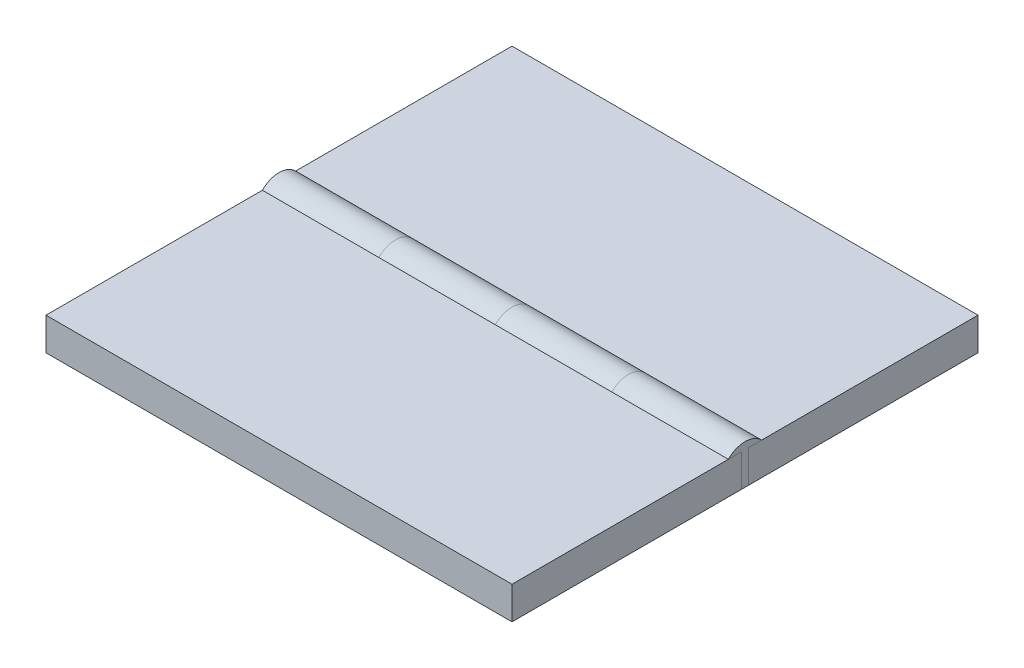
SolidWorks part; units mm, degrees
ref_plane "Front Plane" through (0, 0, 0) normal (0, 0, 1) x (1, 0, 0)
ref_plane "Top Plane" through (0, 0, 0) normal (0, 1, 0) x (1, 0, 0)
ref_plane "Right Plane" through (0, 0, 0) normal (1, 0, 0) x (0, 0, -1)
sketch "Sketch1" plane through (0, 0, 0) normal (1, 0, 0) x (0, 0, -1)
  line L0 (0, 0) -> (0.75, 0) construction
  line L1 (-50, -3.5) -> (-0.75, -3.5)
  line L2 (-50, -3.5) -> (-50, 3.5)
  line L3 (-50, 3.5) -> (-0.75, 3.5)
  line L4 (50, -3.5) -> (50, 3.5)
  line L5 (-50, -3.5) -> (50, 3.5) construction
  line L6 (-50, 3.5) -> (50, -3.5) construction
  line L7 (0.75, 3.5) -> (0.75, -3.5)
  line L8 (0, 0) -> (-0.75, 0) construction
  line L9 (-0.75, -3.5) -> (-0.75, 3.5)
  line L10 (0.75, 3.5) -> (50, 3.5)
  line L11 (0.75, -3.5) -> (50, -3.5)
  line L12 (-0.75, -3.5) -> (0.75, -3.5)
  arc A0 (3.5707, 3.5) -> (-3.5707, 3.5) centre (0, 0) ccw
  point P0 (0, 0)
  dimension "D5" = 10
  dimension "D1" = 100
  dimension "D2" = 7
  dimension "D3" = 0.75
  dimension "D4" = 0.75
extrude "Boss-Extrude1" add sketch "Sketch1" along normal blind 100 contours L1 L9 L3 L2 | L7 L11 L4 L10
sketch "Sketch2" plane through (0, 0, 0) normal (-1, 0, 0) x (0, 0, 1)
  line L0 (0.75, -3.5) -> (-0.75, -3.5) construction
  line L1 (-0.75, 3.5) -> (-0.75, -3.5) construction
  line L2 (-0.75, 3.5) -> (-50, 3.5) construction
  line L3 (-50, -3.5) -> (-50, 3.5) construction
  line L4 (-0.75, -3.5) -> (-50, -3.5) construction
  line L5 (50, -3.5) -> (0.75, -3.5) construction
  line L6 (50, -3.5) -> (50, 3.5) construction
  line L7 (50, 3.5) -> (0.75, 3.5) construction
  line L8 (0.75, -3.5) -> (0.75, 3.5) construction
  line L9 (0.75, -3.5) -> (-0.75, -3.5)
  line L10 (-0.75, 3.5) -> (-0.75, -3.5)
  line L11 (-0.75, 3.5) -> (-50, 3.5)
  line L12 (-50, -3.5) -> (-50, 3.5)
  line L13 (-0.75, -3.5) -> (-50, -3.5)
  line L14 (50, -3.5) -> (0.75, -3.5)
  line L15 (50, -3.5) -> (50, 3.5)
  line L16 (50, 3.5) -> (0.75, 3.5)
  line L17 (0.75, -3.5) -> (0.75, 3.5)
  arc A0 (3.5707, 3.5) -> (-3.5707, 3.5) centre (0, 0) ccw construction
  arc A1 (3.5707, 3.5) -> (-3.5707, 3.5) centre (0, 0) ccw
  line M1 (-0.75, -3.5) -> (-0.75, 3.5)
  line M2 (-0.75, 3.5) -> (-50, 3.5)
extrude "Boss-Extrude2" add sketch "Sketch2" against normal blind 25 separate body contours L16 A1 L9 L17 M2 M1
sketch "Sketch3" plane through (25, 0, 0) normal (1, 0, 0) x (0, 0, -1)
  line L5 (-3.5707, 3.5) -> (-0.75, 3.5)
  line L6 (-0.75, 3.5) -> (-0.75, -3.5)
  line L7 (-0.75, -3.5) -> (0.75, -3.5)
  line L8 (0.75, -3.5) -> (0.75, 3.5)
  line L9 (0.75, 3.5) -> (3.5707, 3.5)
  line L10 (-3.5707, 3.5) -> (-0.75, 3.5)
  line L11 (-0.75, 3.5) -> (-0.75, -3.5)
  line L12 (-0.75, -3.5) -> (0.75, -3.5)
  line L13 (0.75, -3.5) -> (0.75, 3.5)
  line L14 (0.75, 3.5) -> (3.5707, 3.5)
  arc A1 (3.5707, 3.5) -> (-3.5707, 3.5) centre (0, 0) ccw
  arc A2 (3.5707, 3.5) -> (-3.5707, 3.5) centre (0, 0) ccw
  dimension "D1" = 0
extrude "Boss-Extrude3" add sketch "Sketch3" along normal blind 25 separate body
sketch "Sketch4" plane through (50, 0, 0) normal (1, 0, 0) x (0, 0, -1)
  line L5 (-3.5707, 3.5) -> (-0.75, 3.5)
  line L6 (-0.75, 3.5) -> (-0.75, -3.5)
  line L7 (-0.75, -3.5) -> (0.75, -3.5)
  line L8 (0.75, -3.5) -> (0.75, 3.5)
  line L9 (0.75, 3.5) -> (3.5707, 3.5)
  line L10 (-3.5707, 3.5) -> (-0.75, 3.5)
  line L11 (-0.75, 3.5) -> (-0.75, -3.5)
  line L12 (-0.75, -3.5) -> (0.75, -3.5)
  line L13 (0.75, -3.5) -> (0.75, 3.5)
  line L14 (0.75, 3.5) -> (3.5707, 3.5)
  arc A1 (3.5707, 3.5) -> (-3.5707, 3.5) centre (0, 0) ccw
  arc A2 (3.5707, 3.5) -> (-3.5707, 3.5) centre (0, 0) ccw
  dimension "D1" = 0
extrude "Boss-Extrude4" add sketch "Sketch4" along normal blind 25 separate body
sketch "Sketch5" plane through (75, 0, 0) normal (1, 0, 0) x (0, 0, -1)
  line L5 (-3.5707, 3.5) -> (-0.75, 3.5)
  line L6 (-0.75, 3.5) -> (-0.75, -3.5)
  line L7 (-0.75, -3.5) -> (0.75, -3.5)
  line L8 (0.75, -3.5) -> (0.75, 3.5)
  line L9 (0.75, 3.5) -> (3.5707, 3.5)
  line L10 (-3.5707, 3.5) -> (-0.75, 3.5)
  line L11 (-0.75, 3.5) -> (-0.75, -3.5)
  line L12 (-0.75, -3.5) -> (0.75, -3.5)
  line L13 (0.75, -3.5) -> (0.75, 3.5)
  line L14 (0.75, 3.5) -> (3.5707, 3.5)
  arc A1 (3.5707, 3.5) -> (-3.5707, 3.5) centre (0, 0) ccw
  arc A2 (3.5707, 3.5) -> (-3.5707, 3.5) centre (0, 0) ccw
  dimension "D1" = 0
extrude "Boss-Extrude5" add sketch "Sketch5" along normal blind 25 separate body
